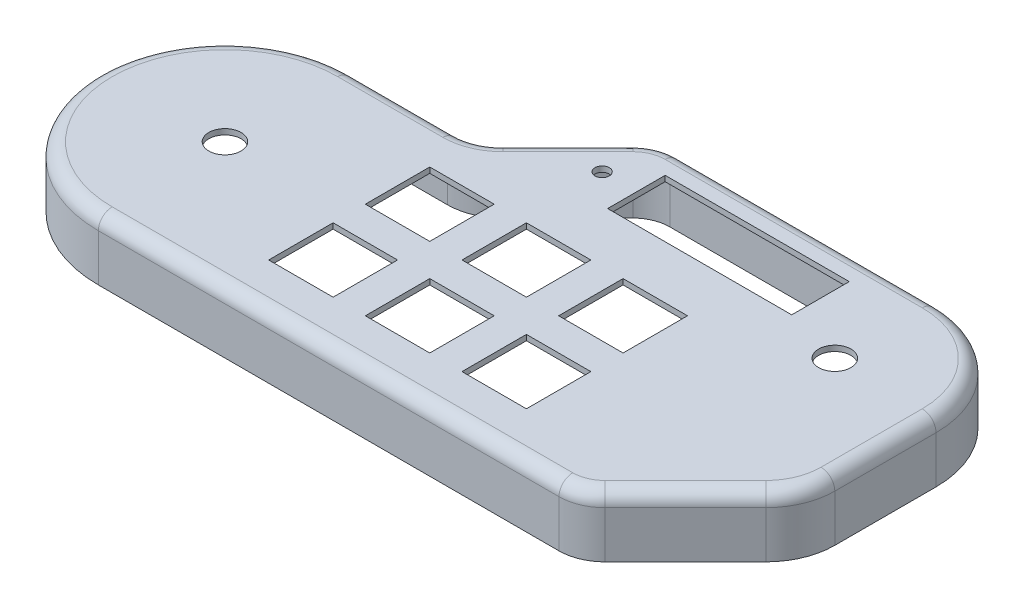
SolidWorks part; units mm, degrees
ref_plane "Front Plane" through (0, 0, 0) normal (0, 0, 1) x (1, 0, 0)
ref_plane "Top Plane" through (0, 0, 0) normal (0, 1, 0) x (1, 0, 0)
ref_plane "Right Plane" through (0, 0, 0) normal (1, 0, 0) x (0, 0, -1)
sketch "Sketch1" plane through (0, 0, 0) normal (0, 1, 0) x (1, 0, 0)
  line L0 (0, 0) -> (-126.4746, 0) construction
  line L1 (-77.0653, 24) -> (-63.0653, 24)
  line L2 (-98.0653, 24) -> (-84.0653, 24)
  line L3 (-98.0653, 24) -> (-98.0653, 10)
  line L4 (-98.0653, 10) -> (-84.0653, 10)
  line L5 (-84.0653, 24) -> (-84.0653, 10)
  line L6 (-63.0653, 24) -> (-63.0653, 10)
  line L7 (-77.0653, 10) -> (-63.0653, 10)
  line L8 (-77.0653, 24) -> (-77.0653, 10)
  line L9 (-56.0653, 24) -> (-42.0653, 24)
  line L10 (-42.0653, 24) -> (-42.0653, 10)
  line L11 (-56.0653, 10) -> (-42.0653, 10)
  line L12 (-56.0653, 24) -> (-56.0653, 10)
  line L13 (-77.0653, 45) -> (-63.0653, 45)
  line L14 (-63.0653, 45) -> (-63.0653, 31)
  line L15 (-77.0653, 31) -> (-63.0653, 31)
  line L16 (-77.0653, 45) -> (-77.0653, 31)
  line L17 (-56.0653, 45) -> (-42.0653, 45)
  line L18 (-42.0653, 45) -> (-42.0653, 31)
  line L19 (-56.0653, 31) -> (-42.0653, 31)
  line L20 (-56.0653, 45) -> (-56.0653, 31)
  line L21 (-98.0653, 45) -> (-84.0653, 45)
  line L22 (-84.0653, 45) -> (-84.0653, 31)
  line L23 (-98.0653, 31) -> (-84.0653, 31)
  line L24 (-98.0653, 45) -> (-98.0653, 31)
  line L25 (-125.0653, 55) -> (-98.0653, 55)
  line L26 (-98.0653, 55) -> (-78.0653, 75)
  line L27 (-78.0653, 75) -> (-18.0653, 75)
  line L28 (-18.0653, 75) -> (-18.0653, 31.7596) construction
  line L29 (-125.0653, 0) -> (-25.7348, 0)
  line L30 (-25.7348, 0) -> (-20.8521, 0)
  line L32 (3.9347, 53) -> (3.9347, 31)
  line L33 (-20.8521, 0) -> (-0.4587, 20.3934)
  circle A0 centre (-125.0653, 27.5) radius 3.5
  arc A1 (-125.0653, 0) -> (-125.0653, 55) centre (-125.0653, 27.5) cw
  arc A2 (-18.0653, 75) -> (3.9347, 53) centre (-18.0653, 53) cw
  circle A3 centre (-18.0653, 53) radius 3.5
  arc A4 (3.9347, 31) -> (-0.4587, 20.3934) centre (-11.0653, 31) cw
  dimension "D5" = 7
  dimension "D6" = 17.5
  dimension "D7" = 27
  dimension "D10" = 45
  dimension "D16" = 7
  dimension "D17" = 22
  dimension "D18" = 15
  dimension "D1" = 14
  dimension "D2" = 14
  dimension "D8" = 10
  dimension "D9" = 45
  dimension "D11" = 27
  dimension "D12" = 60
  dimension "D13" = 7
  dimension "D14" = 20
  dimension "D15" = 7
  dimension "D3" = 3
  dimension "D4" = 2
extrude "Boss-Extrude1" add sketch "Sketch1" along normal blind 1.2
fillet "Fillet1" radius 10 3 edges at (-20.8521, 0.6, 0) (-98.0653, 0.6, -55) (-78.0653, 0.6, -75)
sketch "Sketch3" plane through (0, 0, 0) normal (0, -1, 0) x (1, 0, 0)
  line L12 (-1.8729, -21.8076) -> (-19.3374, -4.3431)
  line L13 (-24.9943, -2) -> (-125.0653, -2)
  line L14 (-125.0653, -53) -> (-102.2075, -53)
  line L15 (-93.7222, -56.5147) -> (-79.58, -70.6569)
  line L16 (-73.9232, -73) -> (-18.0653, -73)
  line L17 (1.9347, -53) -> (1.9347, -31)
  line L18 (-1.8729, -21.8076) -> (-19.3374, -4.3431)
  line L19 (-24.9943, -2) -> (-125.0653, -2)
  line L20 (-125.0653, -53) -> (-102.2075, -53)
  line L21 (-93.7222, -56.5147) -> (-79.58, -70.6569)
  line L22 (-73.9232, -73) -> (-18.0653, -73)
  line L23 (1.9347, -53) -> (1.9347, -31)
  line L30 (-0.4587, -20.3934) -> (-17.9232, -2.9289)
  line L31 (-24.9943, 0) -> (-125.0653, 0)
  line L32 (-125.0653, -55) -> (-102.2075, -55)
  line L33 (-95.1364, -57.9289) -> (-80.9943, -72.0711)
  line L34 (-73.9232, -75) -> (-18.0653, -75)
  line L35 (3.9347, -53) -> (3.9347, -31)
  line L36 (-0.4587, -20.3934) -> (-17.9232, -2.9289)
  line L37 (-24.9943, 0) -> (-125.0653, 0)
  line L38 (-125.0653, -55) -> (-102.2075, -55)
  line L39 (-95.1364, -57.9289) -> (-80.9943, -72.0711)
  line L40 (-73.9232, -75) -> (-18.0653, -75)
  line L41 (3.9347, -53) -> (3.9347, -31)
  arc A12 (-19.3374, -4.3431) -> (-24.9943, -2) centre (-24.9943, -10) ccw
  arc A13 (-125.0653, -2) -> (-125.0653, -53) centre (-125.0653, -27.5) ccw
  arc A14 (-93.7222, -56.5147) -> (-102.2075, -53) centre (-102.2075, -65) ccw
  arc A15 (-79.58, -70.6569) -> (-73.9232, -73) centre (-73.9232, -65) ccw
  arc A16 (-18.0653, -73) -> (1.9347, -53) centre (-18.0653, -53) ccw
  arc A17 (1.9347, -31) -> (-1.8729, -21.8076) centre (-11.0653, -31) ccw
  arc A18 (-19.3374, -4.3431) -> (-24.9943, -2) centre (-24.9943, -10) ccw
  arc A19 (-125.0653, -2) -> (-125.0653, -53) centre (-125.0653, -27.5) ccw
  arc A20 (-93.7222, -56.5147) -> (-102.2075, -53) centre (-102.2075, -65) ccw
  arc A21 (-79.58, -70.6569) -> (-73.9232, -73) centre (-73.9232, -65) ccw
  arc A22 (-18.0653, -73) -> (1.9347, -53) centre (-18.0653, -53) ccw
  arc A23 (1.9347, -31) -> (-1.8729, -21.8076) centre (-11.0653, -31) ccw
  arc A30 (-17.9232, -2.9289) -> (-24.9943, 0) centre (-24.9943, -10) ccw
  arc A31 (-125.0653, 0) -> (-125.0653, -55) centre (-125.0653, -27.5) ccw
  arc A32 (-95.1364, -57.9289) -> (-102.2075, -55) centre (-102.2075, -65) ccw
  arc A33 (-80.9943, -72.0711) -> (-73.9232, -75) centre (-73.9232, -65) ccw
  arc A34 (-18.0653, -75) -> (3.9347, -53) centre (-18.0653, -53) ccw
  arc A35 (3.9347, -31) -> (-0.4587, -20.3934) centre (-11.0653, -31) ccw
  arc A36 (-17.9232, -2.9289) -> (-24.9943, 0) centre (-24.9943, -10) ccw
  arc A37 (-125.0653, 0) -> (-125.0653, -55) centre (-125.0653, -27.5) ccw
  arc A38 (-95.1364, -57.9289) -> (-102.2075, -55) centre (-102.2075, -65) ccw
  arc A39 (-80.9943, -72.0711) -> (-73.9232, -75) centre (-73.9232, -65) ccw
  arc A40 (-18.0653, -75) -> (3.9347, -53) centre (-18.0653, -53) ccw
  arc A41 (3.9347, -31) -> (-0.4587, -20.3934) centre (-11.0653, -31) ccw
  line M46 (-0.4587, -20.3934) -> (-17.9232, -2.9289)
  arc M47 (-17.9232, -2.9289) -> (-24.9943, 0) centre (-24.9943, -10) ccw
  line M48 (-24.9943, 0) -> (-125.0653, 0)
  arc M49 (-125.0653, 0) -> (-125.0653, -55) centre (-125.0653, -27.5) ccw
  line M50 (-125.0653, -55) -> (-102.2075, -55)
  arc M51 (-102.2075, -55) -> (-95.1364, -57.9289) centre (-102.2075, -65) cw
  line M52 (-95.1364, -57.9289) -> (-80.9943, -72.0711)
  arc M53 (-80.9943, -72.0711) -> (-73.9232, -75) centre (-73.9232, -65) ccw
  line M54 (-73.9232, -75) -> (-18.0653, -75)
  arc M55 (-18.0653, -75) -> (3.9347, -53) centre (-18.0653, -53) ccw
  line M56 (3.9347, -53) -> (3.9347, -31)
  arc M57 (3.9347, -31) -> (-0.4587, -20.3934) centre (-11.0653, -31) ccw
  dimension "D1" = 2
  dimension "D2" = 0
extrude "Boss-Extrude2" add sketch "Sketch3" along normal blind 12 contours A23 L23 A22 L22 A21 L21 A20 L20 A19 L19 A18 L18 M57 M46 M47 M48 M49 M50 M51 M52 M53 M54 M55 M56 | L36 A36 L37 A37 L38 A38 L39 A39 L40 A40 L41 A41
fillet "Fillet2" radius 3 12 edges at (-77.75, 1.2, -74.2388) (-45.9943, 1.2, -75) (-2.509, 1.2, -68.5563) (3.9347, 1.2, -42) (2.7929, 1.2, -25.2597) (-9.191, 1.2, -11.6612) (-21.1674, 1.2, -0.7612) (-75.0298, 1.2, 0) (-152.5653, 1.2, -27.5) (-113.6364, 1.2, -55) (-98.3806, 1.2, -55.7612) (-88.0653, 1.2, -65)
fillet "Fillet3" radius 1 12 edges at (-76.9847, 0, -72.391) (-86.6511, 0, -63.5858) (-97.6153, 0, -53.9134) (-113.6364, 0, -53) (-150.5653, 0, -27.5) (-75.0298, 0, -2) (-21.9328, 0, -2.609) (-10.6052, 0, -13.0754) (0.9451, 0, -26.0251) (1.9347, 0, -42) (-3.9232, 0, -67.1421) (-45.9943, 0, -73)
sketch "Sketch4" plane through (0, 1.2, 0) normal (0, 1, 0) x (1, 0, 0)
  line L0 (-18.0653, 72) -> (-73.9232, 72) construction
  line L1 (-70.9232, 69) -> (-30.9232, 69)
  line L2 (-70.9232, 69) -> (-70.9232, 56.5)
  line L3 (-70.9232, 56.5) -> (-30.9232, 56.5)
  line L4 (-30.9232, 69) -> (-30.9232, 56.5)
  line L5 (-70.9232, 62.75) -> (-85.944, 62.8787) construction
  line L6 (-78.8729, 69.9497) -> (-93.0151, 55.8076) construction
  circle A0 centre (-78.4336, 62.8143) radius 1.5625
  dimension "D5" = 3.125
  dimension "D1" = 12.5
  dimension "D2" = 40
  dimension "D3" = 3
  dimension "D4" = 3
extrude "Cut-Extrude1" cut sketch "Sketch4" against normal through all
